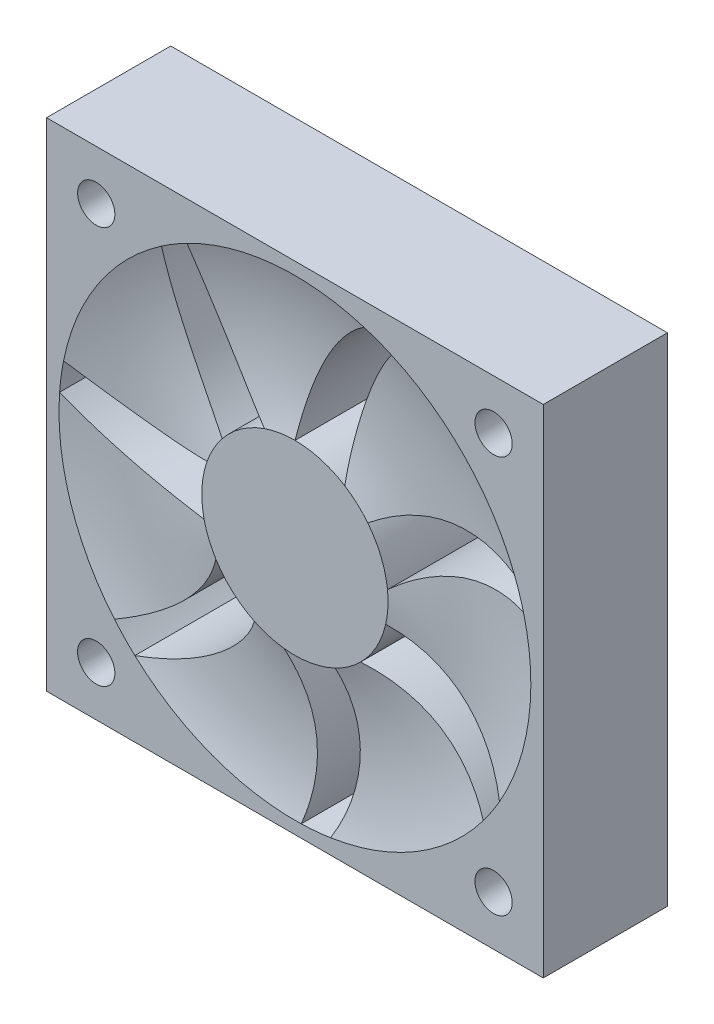
SolidWorks part; units mm, degrees
material "ABS"
ref_plane "Plan de face" through (0, 0, 0) normal (0, 0, 1) x (1, 0, 0)
ref_plane "Plan de dessus" through (0, 0, 0) normal (0, 1, 0) x (1, 0, 0)
ref_plane "Plan de droite" through (0, 0, 0) normal (1, 0, 0) x (0, 0, -1)
sketch "Esquisse1" plane through (0, 0, 0) normal (0, 0, 1) x (1, 0, 0)
  line L0 (0, 20) -> (0, -20) construction
  line L1 (-20, -20) -> (20, -20)
  line L2 (-20, -20) -> (-20, 20)
  line L3 (-20, 20) -> (20, 20)
  line L4 (20, -20) -> (20, 20)
  line L5 (-20, 20) -> (0, 0) construction
  line L6 (20, 0) -> (-20, 0) construction
  circle A0 centre (-16, 16) radius 1.5
  circle A1 centre (16, 16) radius 1.5
  circle A2 centre (16, -16) radius 1.5
  circle A3 centre (-16, -16) radius 1.5
  dimension "D1" = 40
  dimension "D2" = 32
  dimension "D3" = 3
extrude "Boss.-Extru.1" add sketch "Esquisse1" along normal blind 10
sketch "Esquisse2" plane through (0, 0, 10) normal (0, 0, 1) x (1, 0, 0)
  line L1 (20, -20) -> (20, 20) construction
  arc A0 (4.0138, 6.3356) -> (0.0089, 7.5) centre (0, 0) ccw
  arc A1 (7.7836, 17.3325) -> (5.5585, 18.1687) centre (0, 0) ccw
  arc A2 (5.5585, 18.1687) -> (0.0089, 7.5) centre (14, 7) ccw
  arc A3 (7.7836, 17.3325) -> (4.0138, 6.3356) centre (20, 7) ccw
  dimension "D1" = 14
  dimension "D2" = 38
  dimension "D3" = 15
  dimension "D4" = 16
  dimension "D5" = 7
  dimension "D6" = 7
  dimension "D7" = 14
extrude "Enlèv. mat.-Extru.1" cut sketch "Esquisse2" against normal through all
ref_axis "Axe1" through (0, 0, -0.5) along (0, 0, 1)
pattern_circular "Répétition circulaire1" count 7 over 360 about axis through (0, 0, 0) along (0, 0, 1) of "Enlèv. mat.-Extru.1"
sketch "Esquisse3" plane through (0, 0, 0) normal (1, 0, 0) x (0, 0, -1)
  line L0 (0, -20) -> (0, 20) construction
  line L2 (0, 19) -> (0, 7.5)
  line L5 (-5, 20) -> (-5, 13.25) construction
  line L7 (-10, 20) -> (0, 20) construction
  line L8 (-5, 13.25) -> (0, 13.25) construction
  line L10 (0.5, 0) -> (-10.5, 0) construction
  line L13 (-10, 19) -> (-10, 7.5)
  arc A0 (0, 19) -> (0, 7.5) centre (19.1556, 13.25) ccw
  arc A1 (-10, 19) -> (-10, 7.5) centre (-29.1556, 13.25) cw
  dimension "D3" = 20
  dimension "D1" = 19
  dimension "D2" = 7.5
revolve "Enlèvement de matière-Révolution1" cut sketch "Esquisse3" angle 360 about axis through (0, 0, -0.5) along (0, 0, 1)
